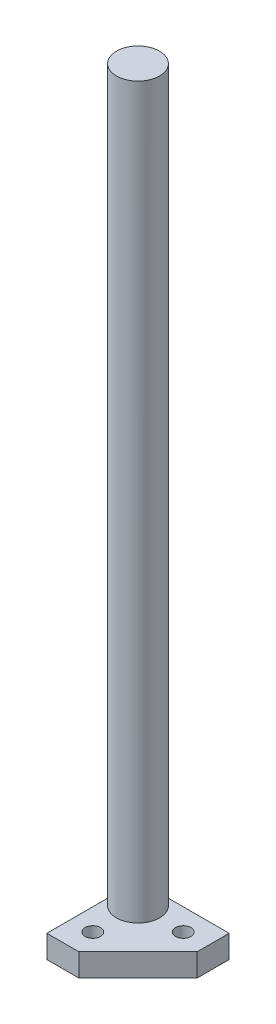
SolidWorks part; units mm, degrees
ref_plane "Front Plane" through (0, 0, 0) normal (0, 0, 1) x (1, 0, 0)
ref_plane "Top Plane" through (0, 0, 0) normal (0, 1, 0) x (1, 0, 0)
ref_plane "Right Plane" through (0, 0, 0) normal (1, 0, 0) x (0, 0, -1)
sketch "Sketch1" plane through (0, 0, 0) normal (0, 1, 0) x (1, 0, 0)
  circle A0 centre (0, 0) radius 3
  dimension "D1" = 6
extrude "Boss-Extrude1" add sketch "Sketch1" along normal blind 101.6
sketch "Sketch3" plane through (0, 0, 0) normal (0, -1, 0) x (1, 0, 0)
  line L0 (-3, 0) -> (-3, 9.7)
  line L1 (-3, 9.7) -> (1.445, 9.7)
  line L2 (1.445, 9.7) -> (9.7, 1.445)
  line L3 (9.7, 1.445) -> (9.7, -3)
  line L4 (9.7, -3) -> (0, -3)
  line L5 (-3, 0) -> (0, 0) construction
  line L6 (0, 0) -> (0, -3) construction
  circle A0 centre (0.048, 6.3498) radius 1.0795
  circle A1 centre (6.3498, 0.048) radius 1.0795
  circle A2 centre (0, 0) radius 3 construction
  arc A3 (-3, 0) -> (0, -3) centre (0, 0) ccw
  dimension "D1" = 2.159
  dimension "D2" = 2.159
  dimension "D3" = 6.35
  dimension "D4" = 6.35
  dimension "D5" = 4.445
  dimension "D6" = 4.445
  dimension "D7" = 12.7
  dimension "D8" = 12.7
  dimension "D9" = 3.048
  dimension "D10" = 3.048
extrude "Boss-Extrude2" add sketch "Sketch3" along normal blind 3.175
equation "\"D2@Sketch3\"=\"D1@Sketch3\""
